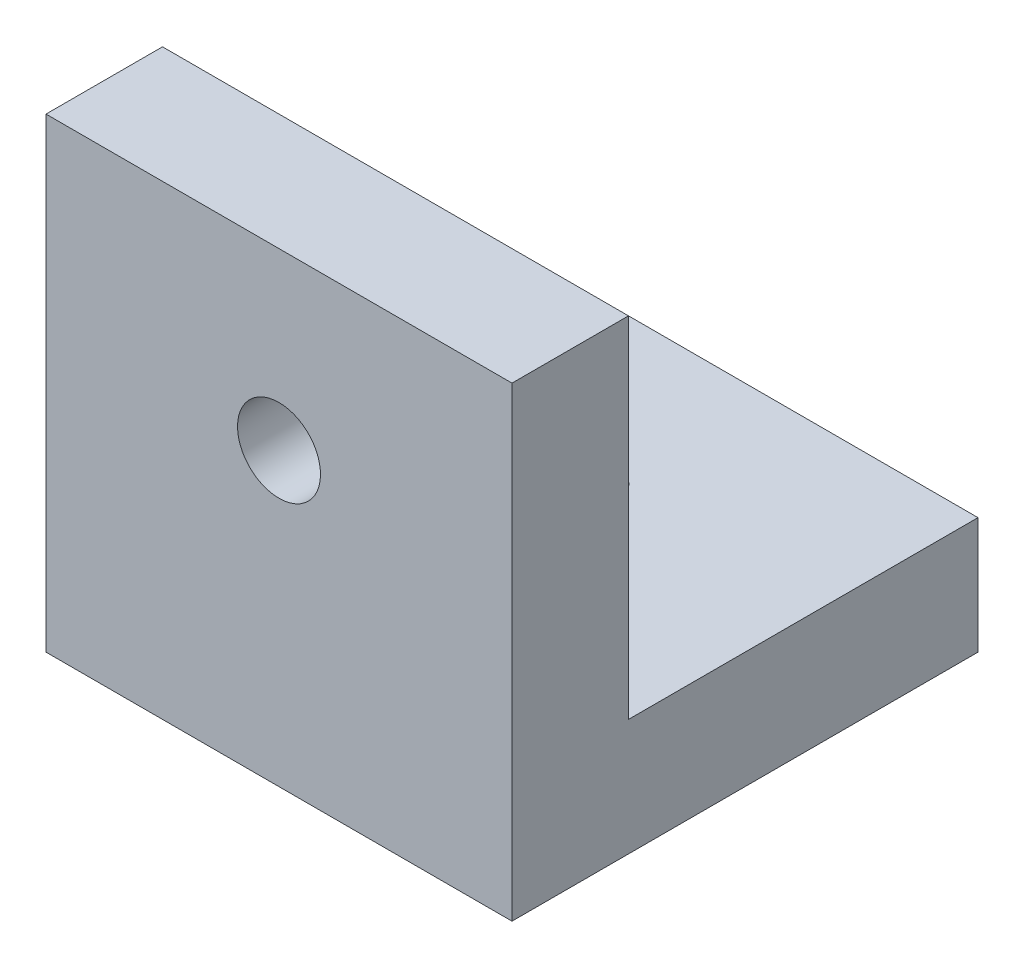
SolidWorks part; units mm, degrees
ref_plane "Front Plane" through (0, 0, 0) normal (0, 0, 1) x (1, 0, 0)
ref_plane "Top Plane" through (0, 0, 0) normal (0, 1, 0) x (1, 0, 0)
ref_plane "Right Plane" through (0, 0, 0) normal (1, 0, 0) x (0, 0, -1)
sketch "Sketch1" plane through (0, 0, 0) normal (1, 0, 0) x (0, 0, -1)
  line L0 (0, 0) -> (0, 12.7)
  line L1 (0, 12.7) -> (3.175, 12.7)
  line L2 (3.175, 12.7) -> (3.175, 3.175)
  line L3 (3.175, 3.175) -> (12.7, 3.175)
  line L4 (12.7, 3.175) -> (12.7, 0)
  line L5 (12.7, 0) -> (0, 0)
  dimension "D1" = 12.7
  dimension "D2" = 12.7
  dimension "D3" = 3.175
  dimension "D4" = 3.175
extrude "Boss-Extrude1" add sketch "Sketch1" along normal blind 12.7
hole_wizard "#43 (0.089) Diameter Hole1" positions "Sketch3" profile "Sketch2" hole size "#43" standard "ANSI Inch"
sketch "Sketch3" plane through (0, 0, -3.175) normal (0, 0, -1) x (-1, 0, 0)
  line L0 (0, 3.175) -> (0, 12.7) construction
  line L1 (-12.7, 12.7) -> (0, 12.7) construction
  point P0 (-6.35, 7.9375)
  dimension "D1" = 6.35
  dimension "D2" = 4.7625
sketch "Sketch2" plane through (6.35, 7.9375, -3.175) normal (1, 0, 0) x (0, 1, 0)
  line L0 (0, 0) -> (0, 26.0792)
  line L1 (0, 26.0792) -> (1.1303, 25.4)
  line L2 (1.1303, 25.4) -> (1.1303, 0)
  line L5 (1.1303, 0) -> (0, 0)
  line L10 (0, 26.0792) -> (-1.1303, 25.4) construction
  line L11 (0, -6.35) -> (0, 107.95) construction
  dimension "Hole Dia." = 2.2606
  dimension "Hole Depth" = 25.4
  dimension "Drill Angle" = 118
hole_wizard "#43 (0.089) Diameter Hole2" positions "Sketch5" profile "Sketch4" hole size "#43" standard "ANSI Inch"
sketch "Sketch5" plane through (0, 3.175, 0) normal (0, 1, 0) x (1, 0, 0)
  line L0 (12.7, 12.7) -> (0, 12.7) construction
  line L1 (0, 12.7) -> (0, 3.175) construction
  point P0 (6.35, 7.9375)
  dimension "D1" = 4.7625
  dimension "D2" = 6.35
sketch "Sketch4" plane through (6.35, 3.175, -7.9375) normal (1, 0, 0) x (0, 0, 1)
  line L0 (0, 0) -> (0, 26.0792)
  line L1 (0, 26.0792) -> (1.1303, 25.4)
  line L2 (1.1303, 25.4) -> (1.1303, 0)
  line L5 (1.1303, 0) -> (0, 0)
  line L10 (0, 26.0792) -> (-1.1303, 25.4) construction
  line L11 (0, -6.35) -> (0, 107.95) construction
  dimension "Hole Dia." = 2.2606
  dimension "Hole Depth" = 25.4
  dimension "Drill Angle" = 118
